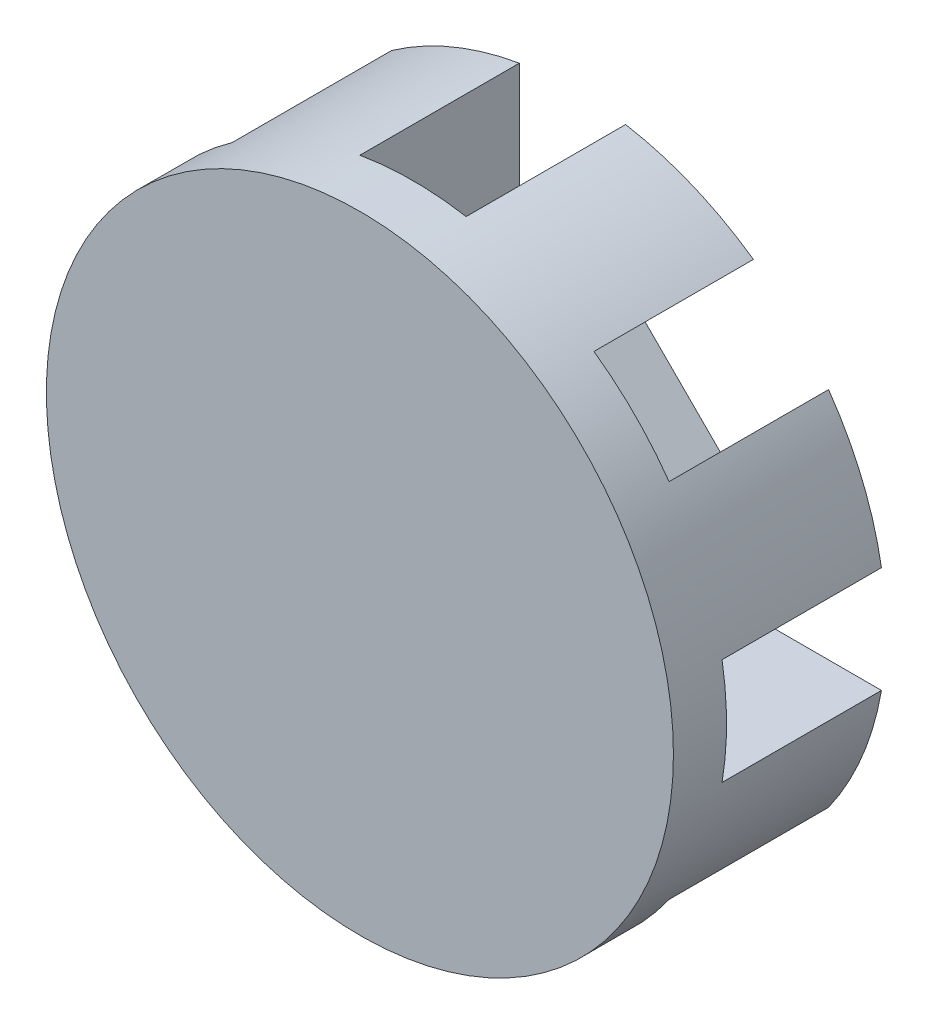
SolidWorks part; units mm, degrees
material "Titanium"
ref_plane "Front Plane" through (0, 0, 0) normal (0, 0, 1) x (1, 0, 0)
ref_plane "Top Plane" through (0, 0, 0) normal (0, 1, 0) x (1, 0, 0)
ref_plane "Right Plane" through (0, 0, 0) normal (1, 0, 0) x (0, 0, -1)
sketch "Sketch1" plane through (0, 0, 0) normal (0, 0, 1) x (1, 0, 0)
  line L0 (1.3542, 2.7886) -> (1.3505, 2.7849)
  line L2 (-1, 5.8146) -> (-1, 2.9343)
  line L3 (-1, 2.9343) -> (1, 2.9343)
  line L4 (1, 5.8146) -> (1, 2.9343)
  line L5 (2.7753, 1.3813) -> (2.7647, 1.3707)
  line L7 (2.9283, 1.0173) -> (2.907, 1.0173)
  line L8 (2.9401, -0.9827) -> (2.907, -0.9827)
  line L10 (2.7853, -1.3609) -> (2.7576, -1.3332)
  line L11 (1.3746, -2.7786) -> (1.3434, -2.7474)
  line L13 (0.99, -2.9377) -> (0.99, -2.8897)
  line L14 (-1.01, -2.9308) -> (-1.01, -2.8897)
  line L16 (-1.3907, -2.7705) -> (-1.3605, -2.7403)
  line L17 (-2.7932, -1.3446) -> (-2.7747, -1.3261)
  line L19 (-2.9434, -0.9727) -> (-2.917, -0.9727)
  line L20 (-2.9248, 1.0273) -> (-2.917, 1.0273)
  line L22 (-2.7739, 1.384) -> (-2.7676, 1.3778)
  line L24 (-1.3595, 2.786) -> (-1.3534, 2.792)
  line L25 (-3.3902, 4.8288) -> (-1.3534, 2.792) [skipped]
  line L26 (1.3505, 2.7849) -> (2.7647, 1.3707) [skipped]
  line L27 (2.907, 1.0173) -> (2.907, -0.9827) [skipped]
  line L28 (2.7576, -1.3332) -> (1.3434, -2.7474) [skipped]
  line L29 (0.99, -2.8897) -> (-1.01, -2.8897) [skipped]
  line L30 (-1.3605, -2.7403) -> (-2.7747, -1.3261) [skipped]
  line L31 (-2.917, -0.9727) -> (-2.917, 1.0273) [skipped]
  arc A1 (-1, 2.9343) -> (1, 2.9343) centre (0, 0) ccw construction
  circle A8 centre (0, 0) radius 5.9
  point P44 (-0.005, 0.0223)
  dimension "D1" = 6.2
  dimension "D2" = 11.8
  dimension "D3" = 2
  dimension "D4" = 8
extrude "Boss-Extrude1" add sketch "Sketch1" along normal blind 4
sketch "Sketch2" plane through (0, 0, 0) normal (0, 0, -1) x (-1, 0, 0)
  line L51 (1, 5.8146) -> (1, 2.9343) construction
  line L52 (1, 2.9343) -> (-1, 2.9343) construction
  line L53 (-1, 5.8146) -> (-1, 2.9343) construction
  line L68 (1, 5.8146) -> (1, 2.9343)
  line L69 (1, 2.9343) -> (-1, 2.9343)
  line L70 (-1, 5.8146) -> (-1, 2.9343)
  circle A9 centre (0, 0) radius 5.9
  arc A10 (1, 5.8146) -> (-1, 5.8146) centre (0, 0) ccw
  dimension "D1" = 0
extrude "Cut-Extrude2" cut sketch "Sketch2" against normal blind 3 contours L70 L69 L68 A10
pattern_circular "CirPattern1" count 8 over 360 about axis through (0, 0, 0) along (0, 0, 1) of "Cut-Extrude2"
